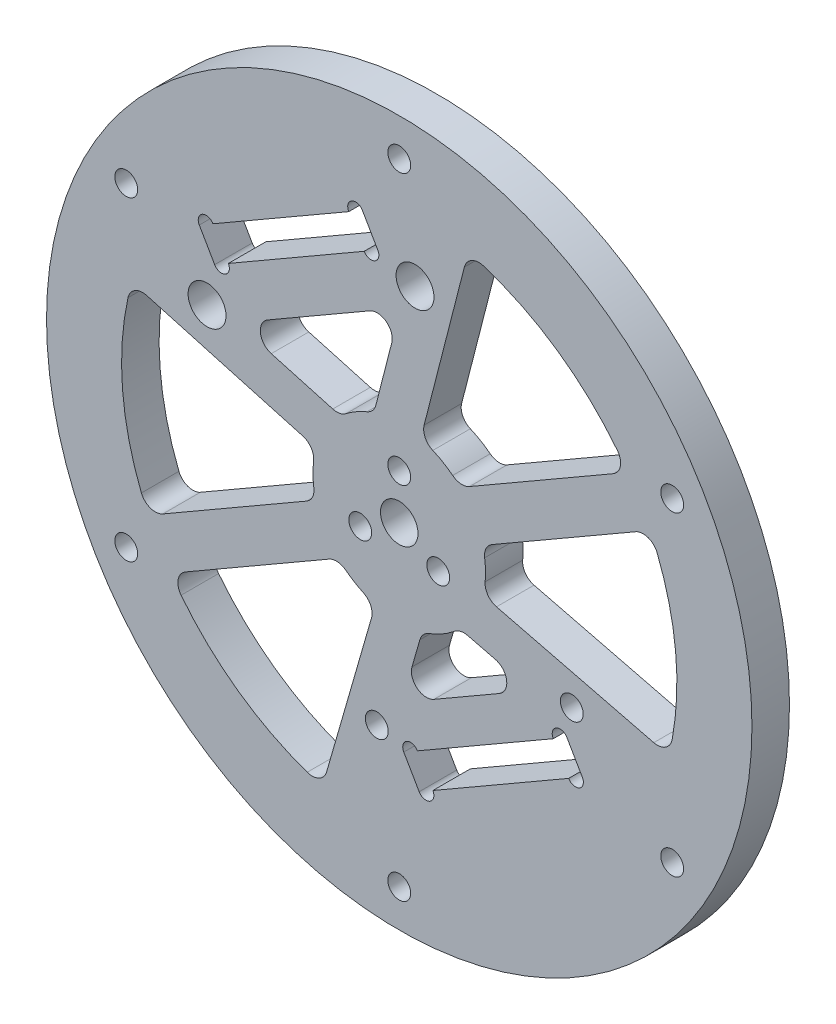
SolidWorks part; units mm, degrees
material "Thornel Mat VMA"
ref_plane "前视基准面" through (0, 0, 0) normal (0, 0, 1) x (1, 0, 0)
ref_plane "上视基准面" through (0, 0, 0) normal (0, 1, 0) x (1, 0, 0)
ref_plane "右视基准面" through (0, 0, 0) normal (1, 0, 0) x (0, 0, -1)
other "Configuration Table"
sketch "草图1" plane through (0, 0, 0) normal (0, 0, 1) x (1, 0, 0)
  circle A0 centre (0, 0) radius 45 construction
  circle A2 centre (0, 0) radius 47
  dimension "D1" = 90
  dimension "D2" = 2
extrude "凸台-拉伸1" add sketch "草图1" along normal blind 5
sketch "草图2" plane through (0, 0, 5) normal (0, 0, 1) x (1, 0, 0)
  circle A0 centre (0, 0) radius 45 construction
  circle A1 centre (0, 0) radius 42 construction
  circle A2 centre (0, 42) radius 1.525
  circle A3 centre (36.3731, 21) radius 1.525
  circle A4 centre (36.3731, -21) radius 1.525
  circle A5 centre (0, -42) radius 1.525
  circle A6 centre (-36.3731, -21) radius 1.525
  circle A7 centre (-36.3731, 21) radius 1.525
  point P19 (0, 0)
  dimension "D1" = 90
  dimension "D3" = 3.05
  dimension "D2" = 3
  dimension "D4" = 6
extrude "切除-拉伸1" cut sketch "草图2" against normal blind 25
sketch "草图4" plane through (0, 0, 5) normal (0, 0, 1) x (1, 0, 0)
  line L0 (22.3253, -13.6686) -> (0.6747, -26.1686) construction
  line L1 (0.6747, -26.1686) -> (2.6747, -29.6327) construction
  line L2 (2.6747, -29.6327) -> (24.3253, -17.1327) construction
  line L3 (24.3253, -17.1327) -> (22.3253, -13.6686) construction
  line L8 (22.3253, -13.6686) -> (0.6747, -26.1686) construction
  line L9 (0.6747, -26.1686) -> (2.6747, -29.6327) construction
  line L10 (2.6747, -29.6327) -> (24.3253, -17.1327) construction
  line L11 (24.3253, -17.1327) -> (22.3253, -13.6686) construction
  line L16 (22.3436, -13.6003) -> (0.6064, -26.1503)
  line L17 (0.6064, -26.1503) -> (2.6564, -29.701)
  line L18 (2.6564, -29.701) -> (24.3936, -17.151)
  line L19 (24.3936, -17.151) -> (22.3436, -13.6003)
  dimension "D1" = 0.05
extrude "切除-拉伸3" cut sketch "草图4" against normal blind 10
sketch "草图5" plane through (0, 0, 5) normal (0, 0, 1) x (1, 0, 0)
  line L2 (22.3436, -13.6003) -> (0.6064, -26.1503) construction
  line L3 (2.6564, -29.701) -> (24.3936, -17.151) construction
  circle A4 centre (21.4343, -14.1253) radius 1.05
  circle A5 centre (23.4843, -17.676) radius 1.05
  circle A6 centre (1.5157, -25.6253) radius 1.05
  circle A7 centre (3.5657, -29.176) radius 1.05
  dimension "D1" = 2.1
extrude "切除-拉伸4" cut sketch "草图5" against normal blind 40
sketch "草图7" plane through (0, 0, 5) normal (0, 0, 1) x (1, 0, 0)
  line L0 (-4.9064, 33.5981) -> (-26.6436, 21.0481)
  line L1 (-26.6436, 21.0481) -> (-24.5936, 17.4974)
  line L2 (-24.5936, 17.4974) -> (-2.8564, 30.0474)
  line L3 (-2.8564, 30.0474) -> (-4.9064, 33.5981)
  line L4 (-4.9247, 33.5298) -> (-26.5753, 21.0298)
  line L5 (-26.5753, 21.0298) -> (-24.5753, 17.5657)
  line L6 (-24.5753, 17.5657) -> (-2.9247, 30.0657)
  line L7 (-2.9247, 30.0657) -> (-4.9247, 33.5298)
  line L8 (-4.9247, 33.5298) -> (-26.5753, 21.0298) construction
  line L9 (-26.5753, 21.0298) -> (-24.5753, 17.5657) construction
  line L10 (-24.5753, 17.5657) -> (-2.9247, 30.0657) construction
  line L11 (-2.9247, 30.0657) -> (-4.9247, 33.5298) construction
  dimension "D1" = 0
  dimension "D2" = 0.05
extrude "切除-拉伸7" cut sketch "草图7" against normal blind 10
sketch "草图8" plane through (0, 0, 5) normal (0, 0, 1) x (1, 0, 0)
  line L0 (-24.5936, 17.4974) -> (-2.8564, 30.0474) construction
  line L1 (-4.9064, 33.5981) -> (-26.6436, 21.0481) construction
  circle A0 centre (-23.6843, 18.0224) radius 1.05
  circle A1 centre (-25.7343, 21.5731) radius 1.05
  circle A2 centre (-5.8157, 33.0731) radius 1.05
  circle A3 centre (-3.7657, 29.5224) radius 1.05
  dimension "D1" = 2.1
extrude "切除-拉伸8" cut sketch "草图8" against normal blind 10
sketch "草图11" plane through (0, 0, 5) normal (0, 0, 1) x (1, 0, 0)
  circle A0 centre (0, 0) radius 6 construction
  circle A1 centre (0, 6) radius 1.525
  circle A2 centre (5.1962, -3) radius 1.525
  circle A3 centre (-5.1962, -3) radius 1.525
  point P11 (0, 0)
  dimension "D1" = 12
  dimension "D2" = 3.05
  dimension "D3" = 3
extrude "切除-拉伸9" cut sketch "草图11" against normal blind 10
sketch "草图12" plane through (0, 0, 0) normal (0, 0, -1) x (-1, 0, 0)
  circle A0 centre (2.9904, -24.8205) radius 1.25 construction
  circle A1 centre (-22.9904, -9.8205) radius 1.25 construction
  circle A2 centre (25.6064, 12.3516) radius 2.1 construction
  circle A3 centre (-2.1064, 28.3516) radius 2.1 construction
  circle A4 centre (2.9904, -24.8205) radius 1.25 construction
  circle A5 centre (-22.9904, -9.8205) radius 1.25 construction
  circle A6 centre (25.6064, 12.3516) radius 2.1 construction
  circle A7 centre (-2.1064, 28.3516) radius 2.1 construction
  circle A8 centre (2.9904, -24.8205) radius 1.525
  circle A9 centre (-22.9904, -9.8205) radius 1.525
  circle A10 centre (-2.1064, 28.3516) radius 2.525
  circle A11 centre (25.6064, 12.3516) radius 2.525
  dimension "D1" = 3.05
  dimension "D2" = 5.05
extrude "切除-拉伸10" cut sketch "草图12" against normal blind 6.5
sketch "草图13" plane through (0, 0, 0) normal (0, 0, -1) x (-1, 0, 0)
  circle A0 centre (0, 0) radius 2.5
  dimension "D1" = 5
extrude "切除-拉伸11" cut sketch "草图13" against normal blind 50
sketch "草图16" plane through (0, 0, 5) normal (0, 0, 1) x (1, 0, 0)
  line L0 (0, 0) -> (-40.4486, 11.3098)
  line L1 (0, 0) -> (-36.3731, -21) construction
  line L2 (0, 0) -> (-11.6309, -40.3574)
  line L3 (-1.5, 2.5981) -> (-37.8731, -18.4019)
  line L4 (1.5, -2.5981) -> (-34.8731, -23.5981)
  line L5 (0, 0) -> (24.8161, -42.9827) construction
  line L6 (0, 0) -> (10.4297, 40.6844)
  line L7 (-1.5, 2.5981) -> (34.8731, 23.5981)
  line L8 (1.5, -2.5981) -> (37.8731, 18.4019)
  line L9 (0, 0) -> (41.7803, -10.3575)
  circle A0 centre (0, 0) radius 37
  circle A1 centre (0, 0) radius 42 construction
  circle A2 centre (-25.6064, 12.3516) radius 2.525 construction
  circle A3 centre (-2.9904, -24.8205) radius 1.525 construction
  circle A4 centre (0, 0) radius 11.5
  circle A5 centre (2.1064, 28.3516) radius 2.525 construction
  circle A6 centre (22.9904, -9.8205) radius 1.525 construction
  dimension "D1" = 5
  dimension "D2" = 5
  dimension "D4" = 23
  dimension "D7" = 5
  dimension "D3" = 4
  dimension "D8" = 4
  dimension "D5" = 3
  dimension "D6" = 3
extrude "切除-拉伸13" cut sketch "草图16" against normal blind 50 contours A4 L9 A0 L8 | A4 L7 A0 L6 | A4 L0 A0 L3 | A4 L4 A0 L2
hole_wizard "M3 十字槽沉头木螺钉的锥形沉头孔1" positions "草图17" profile "草图18" countersink size "M3" standard "GB" end condition through all
sketch "草图17" plane through (0, 0, 0) normal (0, 0, -1) x (-1, 0, 0)
  point P0 (5.1962, -3)
  point P3 (-5.1962, -3)
  point P6 (0, 6)
sketch "草图18" plane through (-5.1962, -3, 0) normal (1, 0, 0) x (0, 1, 0)
  line L0 (0, 0) -> (0, 5)
  line L1 (0, 5) -> (1.5, 5)
  line L2 (1.5, 5) -> (1.5, 1.8)
  line L3 (1.5, 1.8) -> (3.3, 0)
  line L5 (3.3, 0) -> (0, 0)
  line L6 (-1.5, 1.8) -> (-3.3, 0) construction
  line L11 (0, -6.35) -> (0, 107.95) construction
  dimension "通孔孔直径" = 3
  dimension "通孔孔深度" = 5
  dimension "近端锥形沉头孔直径" = 6.6
  dimension "近端锥形沉头孔角度" = 90
sketch "草图19" plane through (0, 0, 0) normal (0, 0, -1) x (-1, 0, 0)
  line L0 (-0.1825, 24.8737) -> (3.3758, 10.9934)
  line L1 (-0.1825, 24.8737) -> (21.6325, 12.2788)
  line L2 (21.6325, 12.2788) -> (7.8326, 8.4202)
  line L3 (11.0752, 3.0967) -> (35.6333, 9.9634) construction
  line L4 (-2.8557, 11.1398) -> (-9.188, 35.841) construction
  line L6 (22.775, 18.5474) -> (4.675, 28.9974) construction
  line L7 (0, 0) -> (36.3731, -21) construction
  circle A0 centre (0, 0) radius 11.5
  dimension "D1" = 23
  dimension "D2" = 6
  dimension "D3" = 6
  dimension "D4" = 6
extrude "切除-拉伸14" cut sketch "草图19" against normal blind 50 contours A0 L2 L1 L0
sketch "草图20" plane through (0, 0, 0) normal (0, 0, -1) x (-1, 0, 0)
  line L0 (-3.0485, -11.0886) -> (-0.3248, -20.5393)
  line L1 (-0.3248, -20.5393) -> (-17.6252, -10.551)
  line L2 (-17.6252, -10.551) -> (-8.0787, -8.1844)
  line L3 (3.1846, -11.0503) -> (10.2462, -35.553) construction
  line L4 (-11.1621, -2.7671) -> (-35.9129, -8.903) construction
  line L5 (-20.525, -14.6503) -> (-2.425, -25.1003) construction
  circle A0 centre (0, 0) radius 11.5
  dimension "D2" = 6
  dimension "D3" = 6
  dimension "D1" = 23
  dimension "D4" = 5
extrude "切除-拉伸15" cut sketch "草图20" against normal blind 50 contours A0 L2 L1 L0
fillet "圆角1" radius 2 24 edges at (-3.1846, -11.0503, 2.5) (0.3248, -20.5393, 2.5) (17.6252, -10.551, 2.5) (3.0485, -11.0886, 2.5) (8.0787, -8.1844, 2.5) (0.1825, 24.8737, 2.5) (-21.6325, 12.2788, 2.5) (-7.8326, 8.4202, 2.5) (-3.3758, 10.9934, 2.5) (-35.6333, 9.9634, 2.5) (-33.4374, -15.841, 2.5) (-11.1144, -2.9528, 2.5) (8.1144, 8.149, 2.5) (30.4374, 21.0372, 2.5) (9.188, 35.841, 2.5) (2.8557, 11.1398, 2.5) (11.1621, -2.7671, 2.5) (35.9129, -8.903, 2.5) (33.4374, 15.841, 2.5) (11.1144, 2.9528, 2.5) (-11.0752, 3.0967, 2.5) (-10.2462, -35.553, 2.5) (-30.4374, -21.0372, 2.5) (-8.1144, -8.149, 2.5)
equation "\"D4@草图19\"=\"D3@草图19\""
equation "\"D3@草图20\"=\"D2@草图20\""
